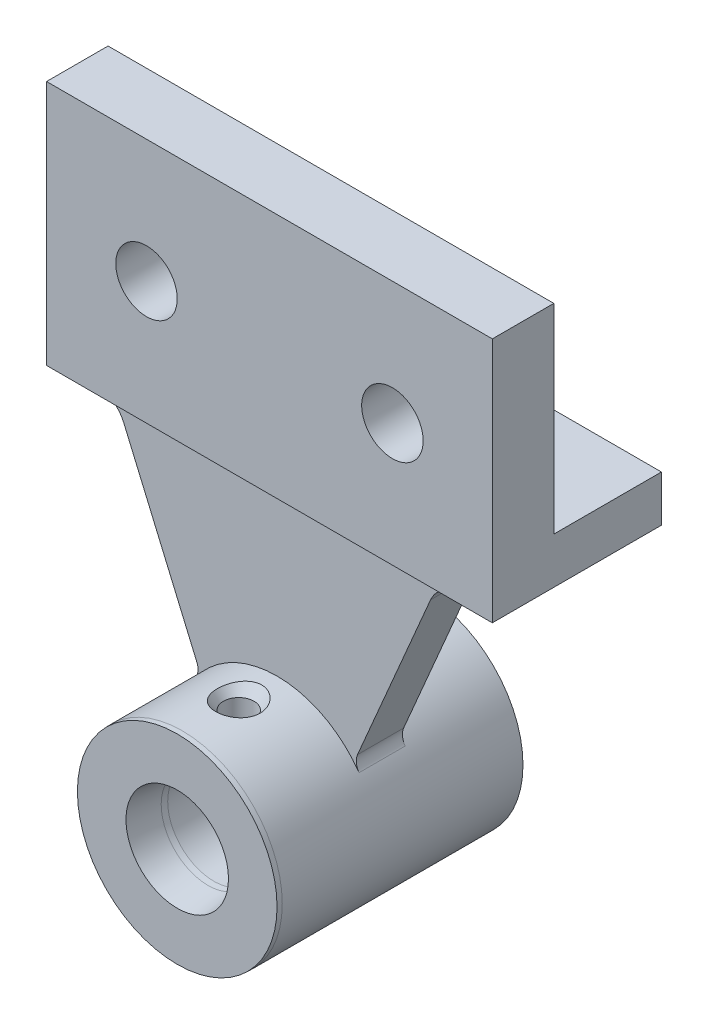
SolidWorks part; units mm, degrees
ref_plane "前视基准面" through (0, 0, 0) normal (0, 0, 1) x (1, 0, 0)
ref_plane "上视基准面" through (0, 0, 0) normal (0, 1, 0) x (1, 0, 0)
ref_plane "右视基准面" through (0, 0, 0) normal (1, 0, 0) x (0, 0, -1)
other "Configuration Table"
sketch "草图1" plane through (0, 0, 0) normal (0, 0, 1) x (1, 0, 0)
  line L1 (-43.5, 24) -> (43.5, 24)
  line L2 (-43.5, 24) -> (-43.5, -24)
  line L3 (-43.5, -24) -> (43.5, -24)
  line L4 (43.5, 24) -> (43.5, -24)
  line L5 (-43.5, 24) -> (43.5, -24) construction
  line L6 (-43.5, -24) -> (43.5, 24) construction
  point P0 (0, 0)
  dimension "D1" = 87
  dimension "D2" = 48
extrude "凸台-拉伸1" add sketch "草图1" against normal blind 12
sketch "草图3" plane through (0, 0, -12) normal (0, 0, -1) x (-1, 0, 0)
  line L0 (43.5, -24) -> (-43.5, -24) construction
  line L1 (-37.5, 15) -> (37.5, 15)
  line L2 (-37.5, 15) -> (-37.5, -15)
  line L3 (-37.5, -15) -> (37.5, -15)
  line L4 (37.5, 15) -> (37.5, -15)
  line L5 (-37.5, 15) -> (37.5, -15) construction
  line L6 (-37.5, -15) -> (37.5, 15) construction
  point P0 (0, 0)
  point P7 (0, 0)
  dimension "D1" = 9
  dimension "D2" = 75
extrude "切除-拉伸1" cut sketch "草图3" against normal blind 3
sketch "草图4" plane through (0, 0, 0) normal (0, 0, 1) x (1, 0, 0)
  line L0 (0, 25.8066) -> (0, -20.5248) construction
  circle A0 centre (24, 0) radius 6
  circle A1 centre (-24, 0) radius 6
  point P4 (0, 0)
  dimension "D2" = 12
  dimension "D3" = 12
  dimension "D1" = 48
extrude "切除-拉伸2" cut sketch "草图4" against normal through all
sketch "草图5" plane through (0, 0, -12) normal (0, 0, -1) x (-1, 0, 0)
  line L0 (-43.5, -24) -> (-43.5, 24) construction
  line L1 (-43.5, -15) -> (43.5, -15)
  line L2 (-43.5, -15) -> (-43.5, -24)
  line L3 (-43.5, -24) -> (43.5, -24)
  line L4 (43.5, -15) -> (43.5, -24)
extrude "凸台-拉伸2" add sketch "草图5" along normal blind 21
ref_plane "基准面1" through (0, 0, -6) normal (0, 0, 1) x (1, 0, 0)
sketch "草图7" plane through (0, 0, -6) normal (0, 0, 1) x (1, 0, 0)
  circle A0 centre (0, -75) radius 19.5
  point P2 (43.5, -15)
  dimension "D1" = 39
  dimension "D2" = 60
extrude "凸台-拉伸3" add sketch "草图7" along normal mid plane 48 separate body
sketch "草图8" plane through (0, 0, -6) normal (0, 0, 1) x (1, 0, 0)
  circle A0 centre (0, -75) radius 9
  dimension "D1" = 18
extrude "切除-拉伸3" cut sketch "草图8" against normal mid plane 34
ref_plane "基准面2" through (0, -75, 0) normal (0, 1, 0) x (1, 0, 0)
sketch "草图10" plane through (0, -75, 0) normal (0, 1, 0) x (1, 0, 0)
  line L0 (0, -18) -> (0, -11)
  line L1 (-19.5, -18) -> (19.5, -18) construction
  line L2 (0, -11) -> (9, -11)
  line L3 (9, -11) -> (10, -18)
  line L4 (10, -18) -> (0, -18)
  dimension "D1" = 9
  dimension "D2" = 10
  dimension "D3" = 7
revolve "切除-旋转1" cut sketch "草图10" angle 360 about L0
mirror "镜向1" about plane through (0, 0, -6) normal (0, 0, 1) of "切除-旋转1"
sketch "草图12" plane through (0, 0, -6) normal (0, 0, 1) x (1, 0, 0)
  line L0 (-29.9422, -27.6386) -> (-15.6874, -60.9344)
  line L2 (0, 24) -> (0, -102.9568) construction
  line L3 (43.5, 24) -> (-43.5, 24) construction
  line L4 (29.9422, -27.6386) -> (15.6874, -60.9344)
  line L5 (-35.458, -24) -> (35.458, -24)
  circle A0 centre (0, -75) radius 19.5 construction
  arc A1 (15.9859, -63.8331) -> (-15.9859, -63.8331) centre (0, -75) ccw
  arc A2 (-29.9422, -27.6386) -> (-35.458, -24) centre (-35.458, -30) ccw
  arc A3 (29.9422, -27.6386) -> (35.458, -24) centre (35.458, -30) cw
  arc A4 (-15.9859, -63.8331) -> (-15.6874, -60.9344) centre (-18.4453, -62.1151) ccw
  arc A5 (15.9859, -63.8331) -> (15.6874, -60.9344) centre (18.4453, -62.1151) cw
  dimension "D1" = 6
  dimension "D3" = 6
  dimension "D4" = 6
extrude "凸台-拉伸4" add sketch "草图12" along normal mid plane 9
ref_plane "基准面3" through (0, -55.5, 0) normal (0, 1, 0) x (1, 0, 0)
sketch "草图13" plane through (0, -55.5, 0) normal (0, 1, 0) x (1, 0, 0)
  line L0 (-19.5, -18) -> (19.5, -18) construction
  circle A0 centre (0, -6) radius 3
  dimension "D1" = 6
  dimension "D2" = 12
extrude "切除-拉伸4" cut sketch "草图13" against normal up to surface (10.7857 mm away)
ref_plane "基准面4" through (0, 0, 6) normal (0, 0, 1) x (1, 0, 0)
sketch "草图14" plane through (0, 0, 6) normal (0, 0, 1) x (1, 0, 0)
  line L0 (0, -55.5) -> (0, -57.5)
  line L1 (13.2, -55.5) -> (-13.2, -55.5) construction
  line L2 (0, -57.5) -> (3, -57.5)
  line L3 (3, -57.5) -> (4.5, -55.5)
  line L4 (4.5, -55.5) -> (0, -55.5)
  dimension "D1" = 2
  dimension "D2" = 4.5
  dimension "D3" = 3
revolve "切除-旋转2" cut sketch "草图14" angle 360 about L0
chamfer "倒角6" distance 1 angle 1 4 edges at (19.5, -75, -30) (19.5, -75, 18) (9, -75, -23) (9, -75, 11)
